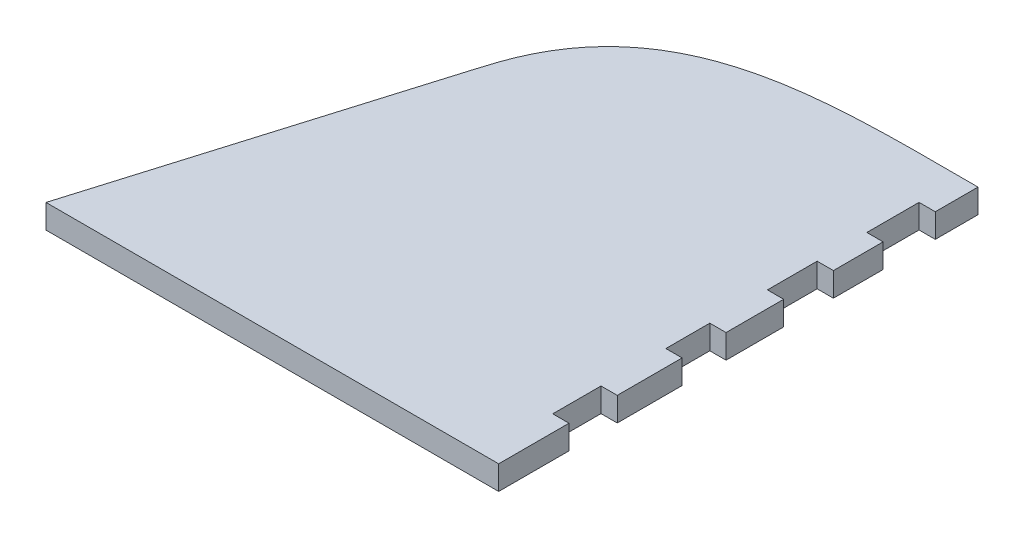
SolidWorks part; units mm, degrees
ref_plane "Front Plane" through (0, 0, 0) normal (0, 0, 1) x (1, 0, 0)
ref_plane "Top Plane" through (0, 0, 0) normal (0, 1, 0) x (1, 0, 0)
ref_plane "Right Plane" through (0, 0, 0) normal (1, 0, 0) x (0, 0, -1)
sketch "Sketch1" plane through (0, 0, 0) normal (0, 1, 0) x (1, 0, 0)
  line L0 (0, 0) -> (107.95, 0)
  line L2 (0, 0) -> (23.435, 78.1099)
  line L6 (138.0478, 114.3) -> (77.8522, 114.3) construction
  line L7 (107.95, 114.3) -> (107.95, 0)
  line L8 (107.95, 104.1138) -> (104.0759, 104.1138)
  line L9 (107.95, 104.1138) -> (107.95, 91.6704)
  line L10 (107.95, 91.6704) -> (104.0759, 91.6704)
  line L11 (104.0759, 104.1138) -> (104.0759, 91.6704)
  line L12 (107.95, 79.8159) -> (104.0759, 79.8159)
  line L13 (107.95, 79.8159) -> (107.95, 67.9614)
  line L14 (107.95, 67.9614) -> (104.0759, 67.9614)
  line L15 (104.0759, 79.8159) -> (104.0759, 67.9614)
  line L16 (107.95, 54.217) -> (104.0759, 54.217)
  line L17 (107.95, 54.217) -> (107.95, 43.737)
  line L18 (107.95, 43.737) -> (104.0759, 43.737)
  line L19 (104.0759, 54.217) -> (104.0759, 43.737)
  line L20 (107.95, 28.2745) -> (104.0759, 28.2745)
  line L21 (107.95, 28.2745) -> (107.95, 16.7636)
  line L22 (107.95, 16.7636) -> (104.0759, 16.7636)
  line L23 (104.0759, 28.2745) -> (104.0759, 16.7636)
  spline S0 degree 3 poles (23.435, 78.1099) (23.9777, 79.9187) (34.8316, 116.0953) (72.2088, 114.3) (107.95, 114.3) knots 0 0 0 0 0.05 1 1 1 1
  dimension "D1" = 107.95
  dimension "D3" = 114.3
extrude "Boss-Extrude1" add sketch "Sketch1" along normal blind 5.715 contours L7 L6 S0 L2 L0 L22 L23 L20 L18 L19 L16 L14 L15 L12 L10 L11 L8
